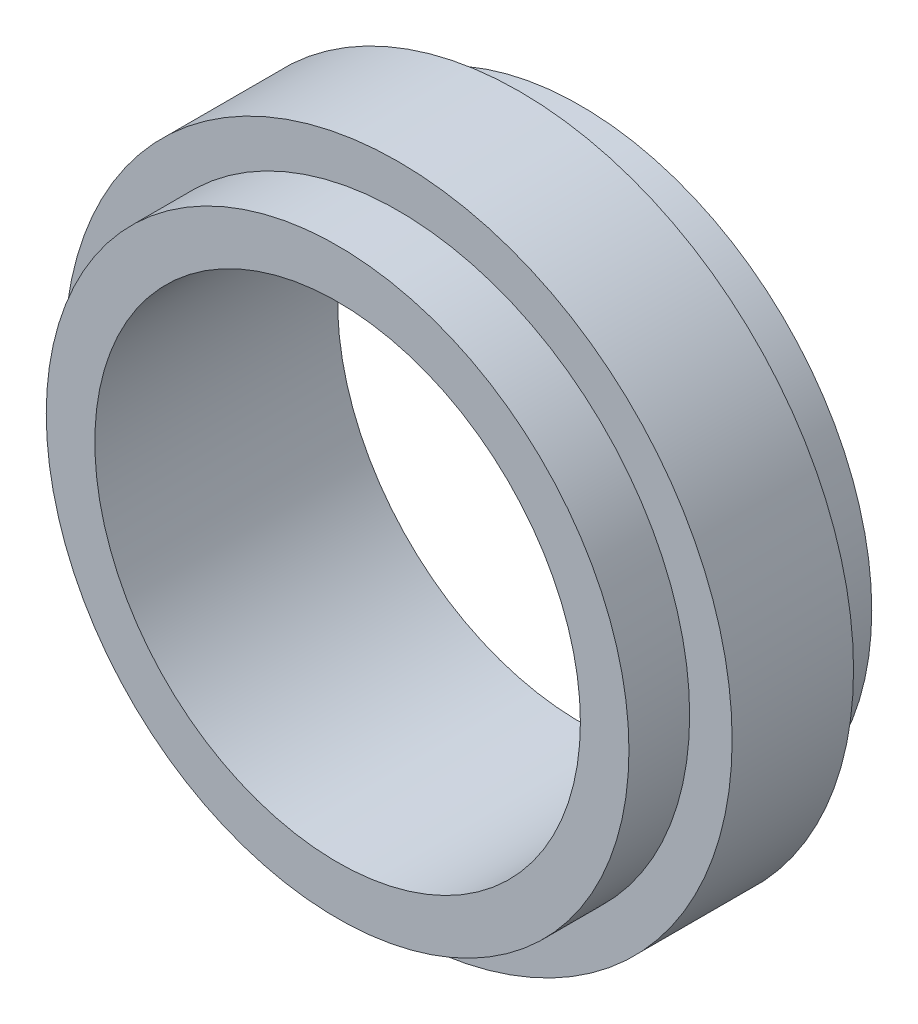
SolidWorks part; units mm, degrees
ref_plane "Front Plane" through (0, 0, 0) normal (0, 0, 1) x (1, 0, 0)
ref_plane "Top Plane" through (0, 0, 0) normal (0, 1, 0) x (1, 0, 0)
ref_plane "Right Plane" through (0, 0, 0) normal (1, 0, 0) x (0, 0, -1)
sketch "Sketch1" plane through (0, 0, 0) normal (0, 0, 1) x (1, 0, 0)
  circle A0 centre (0, 0) radius 20
  circle A1 centre (0, 0) radius 27.5
  dimension "D1" = 40
  dimension "D2" = 55
extrude "Boss-Extrude1" add sketch "Sketch1" along normal mid plane 10
sketch "Sketch2" plane through (0, 0, 5) normal (0, 0, 1) x (1, 0, 0)
  circle A0 centre (0, 0) radius 20 construction
  circle A1 centre (0, 0) radius 20
  circle A2 centre (0, 0) radius 24
  dimension "D1" = 4
extrude "Boss-Extrude2" add sketch "Sketch2" along normal blind 5
mirror "Mirror1" about plane through (0, 0, 0) normal (0, 0, 1) of "Boss-Extrude2"
